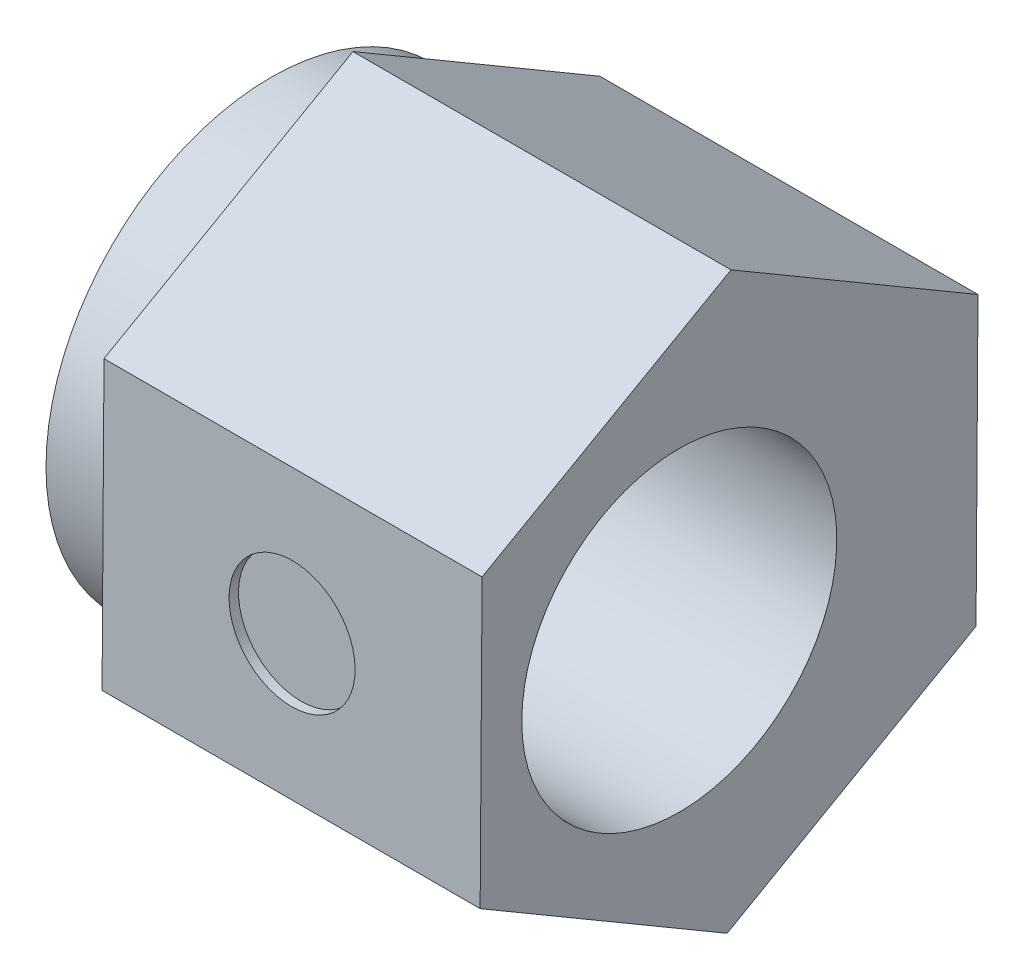
SolidWorks part; units mm, degrees
ref_plane "Front Plane" through (0, 0, 0) normal (0, 0, 1) x (1, 0, 0)
ref_plane "Top Plane" through (0, 0, 0) normal (0, 1, 0) x (1, 0, 0)
ref_plane "Right Plane" through (0, 0, 0) normal (1, 0, 0) x (0, 0, -1)
sketch "Sketch2" plane through (0, 0, 0) normal (1, 0, 0) x (0, 0, -1)
  line L1 (3.9194, -2.2986) -> (3.9504, 2.245)
  line L2 (3.9504, 2.245) -> (0.0309, 4.5436)
  line L3 (0.0309, 4.5436) -> (-3.9194, 2.2986)
  line L4 (-3.9194, 2.2986) -> (-3.9504, -2.245)
  line L5 (-3.9504, -2.245) -> (-0.0309, -4.5436)
  line L6 (-0.0309, -4.5436) -> (3.9194, -2.2986)
  circle A0 centre (0, 0) radius 3.935 construction
  dimension "D1" = 7.87
extrude "Boss-Extrude1" add sketch "Sketch2" along normal blind 6
sketch "Sketch4" plane through (0, 0, 0) normal (-1, 0, 0) x (0, 0, 1)
  circle A0 centre (0, 0) radius 3.57
  dimension "D1" = 7.14
extrude "Boss-Extrude2" add sketch "Sketch4" along normal blind 1.27
sketch "Sketch3" plane through (-1.27, 0, 0) normal (-1, 0, 0) x (0, 0, 1)
  line L0 (0, 0) -> (0.79, 0) construction
  circle A0 centre (0.79, 0) radius 2.5
  dimension "D1" = 5
  dimension "D2" = 0.79
extrude "Cut-Extrude1" cut sketch "Sketch3" against normal through all
sketch "Sketch5" plane through (0, 0.0268, 3.9349) normal (0, -0.0068, -1) x (1, 0, 0)
  line L0 (0, -2.2719) -> (0, 2.2719) construction
  line L6 (0, 0) -> (6, 0) construction
  line L8 (6, -2.2719) -> (6, 2.2719) construction
  circle A0 centre (3, 0) radius 1
  point P5 (0, 0)
  point P8 (6, 0)
  point P10 (3, 0)
  dimension "D1" = 2
extrude "Cut-Extrude3" cut sketch "Sketch5" along normal blind 0.15
